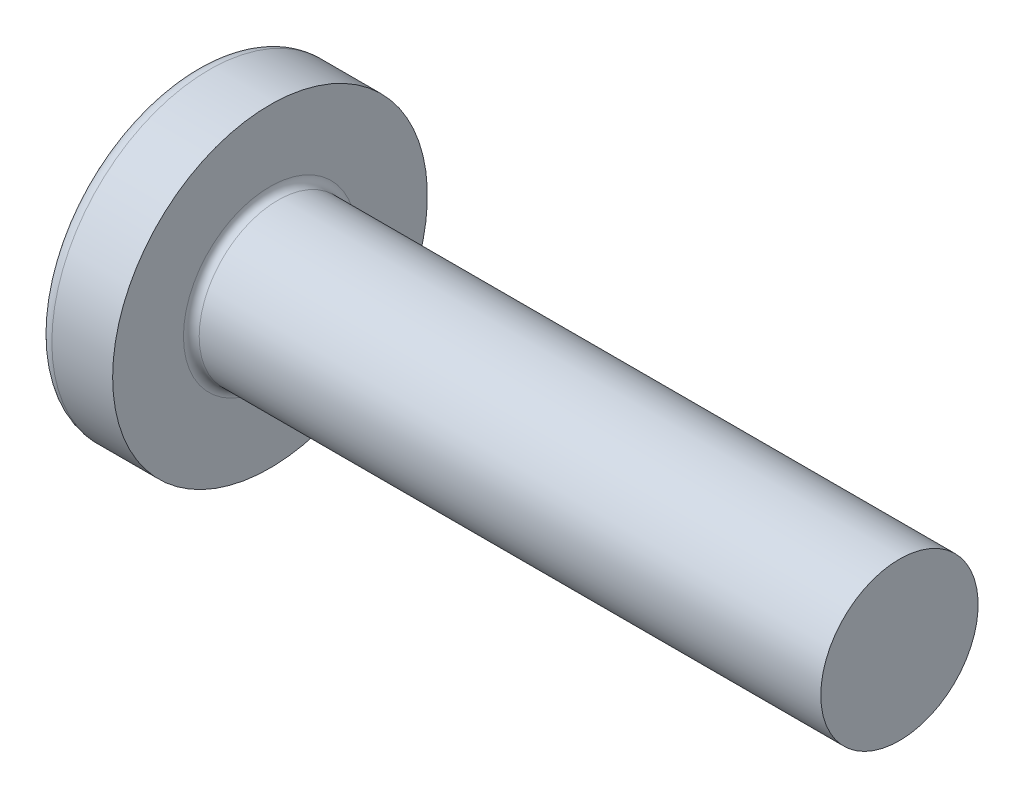
SolidWorks part; units mm, degrees
ref_plane "Plane1" through (0, 0, 0) normal (0, 0, 1) x (1, 0, 0)
ref_plane "Plane2" through (0, 0, 0) normal (0, 1, 0) x (1, 0, 0)
ref_plane "Plane3" through (0, 0, 0) normal (1, 0, 0) x (0, 0, -1)
sketch "BodySke" plane through (0, 0, 0) normal (0, 0, 1) x (1, 0, 0)
  line L0 (3.1, 2) -> (3.1, 4)
  line L1 (3.45, 6.35) -> (3.45, -3.175) construction
  line L2 (-25.4, 0) -> (127, 0) construction
  line L3 (19.1, 0) -> (0, 0)
  line L4 (3.1, 2) -> (19.1, 2)
  line L5 (19.1, 2) -> (19.1, 0)
  line L6 (1.5553, 4) -> (3.1, 4)
  line L8 (3.1, 6.35) -> (3.1, -3.175) construction
  arc A0 (1.2654, 3.8534) -> (0, 0) centre (6.5, 0) ccw
  arc A2 (1.2654, 3.8534) -> (1.5553, 4) centre (1.5553, 3.64) cw
  dimension "Head_crown_rad" = 6.5
  dimension "Head_fillet_rad" = 0.36
  dimension "Length" = 16
  dimension "Head_ht" = 3.1
  dimension "Head_dia" = 8
  dimension "Advance" = 0.7
  dimension "Thread_nom" = 16
  dimension "Diameter" = 4
revolve "Base-Revolve" add sketch "BodySke"
cosmetic thread "ThreadCosmetic" [suppressed]
fillet "Fillet1" radius 0.2 1 edges at (3.1, 0, 2)
sketch "Sketch3" plane through (0, 0, 0) normal (1, 0, 0) x (0, 0, -1)
  line L0 (0.515, -2.15) -> (-0.515, -2.15)
  line L1 (0.515, -2.15) -> (0.515, 2.15)
  line L2 (-0.515, 2.15) -> (0.515, 2.15)
  line L3 (-0.515, 2.15) -> (-0.515, -2.15)
  dimension "Cross_dia" = 4.3
  dimension "D1" = 2.15
  dimension "Cross_width" = 1.03
  dimension "D2" = 0.515
ref_plane "Plane4" through (2.34, 0, 0) normal (1, 0, 0) x (0, 0, -1)
sketch "Sketch4" plane through (2.34, 0, 0) normal (1, 0, 0) x (0, 0, -1)
  line L0 (0.515, -0.9833) -> (-0.515, -0.9833)
  line L1 (0.515, -0.9833) -> (0.515, 0.9833)
  line L2 (-0.515, 0.9833) -> (0.515, 0.9833)
  line L3 (-0.515, 0.9833) -> (-0.515, -0.9833)
  dimension "D1" = 1.03
  dimension "D2" = 1.9666
  dimension "D3" = 0.515
  dimension "D4" = 0.9833
loft "Recess" cut profiles "Sketch3", "Sketch4"
pattern_circular "RecPat" count 2 every 90 about axis through (0, 0, 0) along (1, 0, 0) of "Recess"
sketch "RecCorSke" plane through (0, 0, 0) normal (0, 0, 1) x (1, 0, 0)
  line L0 (-3.175, 0) -> (15.875, 0) construction
  line L1 (-25.4, 0) -> (127, 0) construction
  line L2 (0, 0) -> (0, 1.0146)
  line L3 (0, 1.0146) -> (2.34, 0.851)
  line L4 (2.34, 0.851) -> (2.6165, 0)
  line L5 (2.6165, 0) -> (0, 0)
  dimension "Diameter" = 1.702
  dimension "Depth" = 2.34
  dimension "Draft_angle" = 4
  dimension "Bottom_angle" = 18
revolve "RecessCore" cut sketch "RecCorSke" angle 360 about L0
sketch "ThdSchSke" plane through (0, 0, 0) normal (0, 0, 1) x (1, 0, 0)
  line L0 (4.5, -1.61) -> (4.2269, -2)
  line L1 (4.5, -1.61) -> (4.7731, -2)
  line L2 (4.7731, -2) -> (4.7731, -2.5)
  line L3 (-3.175, 0) -> (5.1513, 0) construction
  line L5 (4.7731, -2.5) -> (4.2269, -2.5)
  line L6 (4.2269, -2.5) -> (4.2269, -2)
  dimension "Diameter" = 4
  dimension "SideAngle" = 55
  dimension "VeeAngle" = 70
  dimension "Thread_minor" = 3.22
  dimension "Overcut" = 5
  dimension "Start" = 4.5
revolve "ThreadSchematic" [suppressed] cut sketch "ThdSchSke" angle 360 about L3
pattern_linear "ThdSchPat" [suppressed]
equation "\"D1@Sketch3\" = \"Cross_dia@Sketch3\" / 2"
equation "\"D2@Sketch3\" = \"Cross_width@Sketch3\" / 2"
equation "\"Depth@RecCorSke\" = \"Cross_depth@Plane4\""
equation "\"D1@Sketch4\" = \"Cross_width@Sketch3\""
equation "\"D2@Sketch4\" = \"Cross_dia@Sketch3\" - 2.0 * \"Cross_depth@Plane4\" * tan(26.5  * 0.017453292)"
equation "\"D3@Sketch4\" = \"D1@Sketch4\" / 2"
equation "\"D4@Sketch4\" = \"D2@Sketch4\" / 2"
equation "\"Thread_length@ThreadCosmetic\" = ((sgn( (\"Length@BodySke\" - \"Advance@BodySke\" * 2.0 ) - \"Thread_nom@BodySke\" )-1)*( (\"Length@BodySke\" - \"Advance@BodySke\" * 2.0 ) - \"Thread_nom@BodySke\" ))/-2+ \"Thread_nom@BodySke\""
equation "\"Thread_minor@ThdSchSke\" = \"Thread_minor@ThreadCosmetic\""
equation "\"Diameter@ThdSchSke\" = \"Diameter@BodySke\""
equation "\"Overcut@ThdSchSke\" = \"Diameter@BodySke\" * 1.25"
equation "\"Start@ThdSchSke\" = \"Head_ht@BodySke\" + \"Length@BodySke\" - \"Thread_length@ThreadCosmetic\"  '---Non-countersunk---"
equation "\"Num_threads@ThdSchPat\" = int( \"Thread_length@ThreadCosmetic\" / \"Advance@BodySke\" + 0.999 )  + 1"
equation "\"Advance@ThdSchPat\" = \"Thread_length@ThreadCosmetic\" /  (\"Num_threads@ThdSchPat\" - 1) 'relax it"
